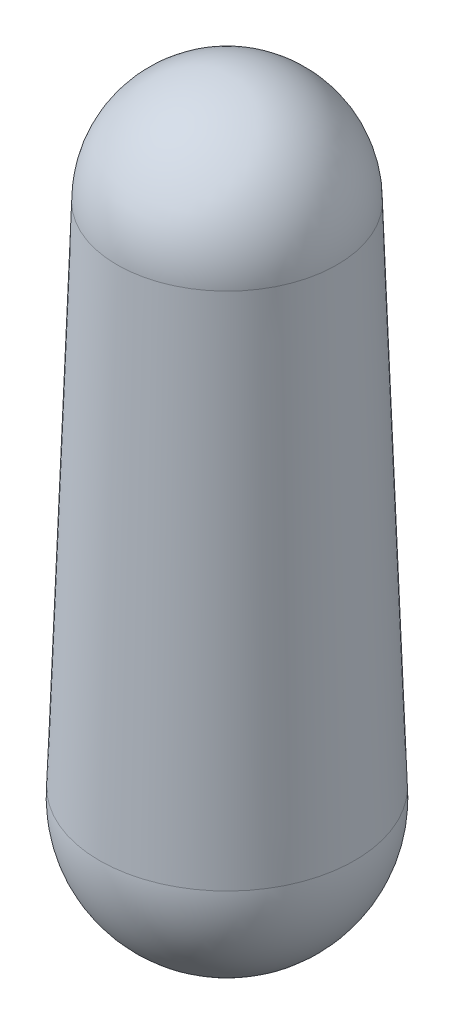
SolidWorks part; units mm, degrees
material "1060 Alloy"
ref_plane "Front Plane" through (0, 0, 0) normal (0, 0, 1) x (1, 0, 0)
ref_plane "Top Plane" through (0, 0, 0) normal (0, 1, 0) x (1, 0, 0)
ref_plane "Right Plane" through (0, 0, 0) normal (1, 0, 0) x (0, 0, -1)
sketch "Sketch1" plane through (0, 0, 0) normal (0, 1, 0) x (1, 0, 0)
  line L0 (0, 2.48) -> (0, -2.48) construction
  line L1 (0, 2.48) -> (0, -2.48)
  arc A0 (0, -2.48) -> (0, 2.48) centre (0, 0) ccw
  dimension "D1" = 4.96
revolve "Revolve1" add sketch "Sketch1" angle 360 about L0
sketch "Sketch2" plane through (0, 0, 0) normal (0, 1, 0) x (1, 0, 0)
  circle A0 centre (0, 0) radius 2.48
  circle A1 centre (0, 0) radius 2.48 construction
extrude "Boss-Extrude1" add sketch "Sketch2" along normal blind 10 draft 2
sketch "Sketch3" plane through (0, 10, 0) normal (0, 1, 0) x (1, 0, 0)
  line L0 (0, 2.1308) -> (0, -2.1308) construction
  line L1 (0, 2.1308) -> (0, -2.1308)
  arc A0 (0, -2.1308) -> (0, 2.1308) centre (0, 0) ccw
  circle A1 centre (0, 0) radius 2.1308 construction
  dimension "D1" = 2.1308
revolve "Revolve2" add sketch "Sketch3" angle 360 about L0
